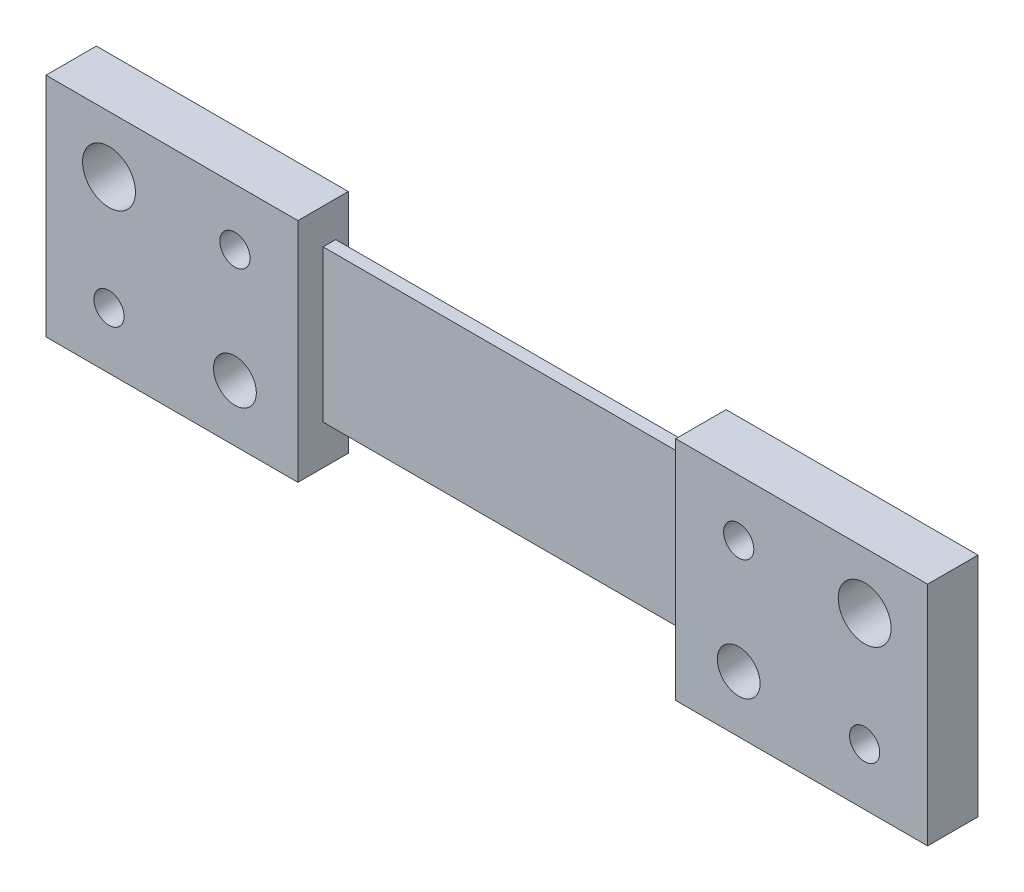
SolidWorks part; units mm, degrees
ref_plane "Спереди" through (0, 0, 0) normal (0, 0, 1) x (1, 0, 0)
ref_plane "Сверху" through (0, 0, 0) normal (0, 1, 0) x (1, 0, 0)
ref_plane "Справа" through (0, 0, 0) normal (1, 0, 0) x (0, 0, -1)
sketch "Эскиз1" plane through (0, 0, 0) normal (0, 0, 1) x (1, 0, 0)
  line L0 (-42.678, 0) -> (49.8614, 0) construction
  line L1 (0, 35.1777) -> (0, -24.4025) construction
  line L2 (15, -9) -> (15, 9)
  line L3 (-35, -9) -> (-15, -9)
  line L4 (-35, -9) -> (-35, 9)
  line L5 (-35, 9) -> (-15, 9)
  line L6 (-15, -9) -> (-15, 9)
  line L7 (35, 9) -> (15, 9)
  line L8 (35, -9) -> (35, 9)
  line L9 (35, -9) -> (15, -9)
  circle A0 centre (-30, 4.5) radius 2.1
  circle A1 centre (-20, 4.5) radius 1.2
  circle A2 centre (-20, -4.5) radius 1.7
  circle A3 centre (-30, -4.5) radius 1.2
  circle A4 centre (30, -4.5) radius 1.2
  circle A5 centre (20, -4.5) radius 1.7
  circle A6 centre (20, 4.5) radius 1.2
  circle A7 centre (30, 4.5) radius 2.1
  dimension "D4" = 4.5
  dimension "D6" = 4.2
  dimension "D7" = 5
  dimension "D8" = 4.5
  dimension "D9" = 2.4
  dimension "D11" = 4.5
  dimension "D12" = 5
  dimension "D13" = 4.5
  dimension "D14" = 3.4
  dimension "D1" = 20
  dimension "D2" = 18
  dimension "D3" = 35
  dimension "D5" = 5
  dimension "D10" = 5
extrude "Вытянуть1" add sketch "Эскиз1" along normal blind 4
cosmetic thread "Условное изображение резьбы1"
cosmetic thread "Условное изображение резьбы2"
cosmetic thread "Условное изображение резьбы3"
cosmetic thread "Условное изображение резьбы4"
cosmetic thread "Условное изображение резьбы5"
cosmetic thread "Условное изображение резьбы6"
cosmetic thread "Условное изображение резьбы7"
cosmetic thread "Условное изображение резьбы8"
ref_plane "Плоскость1" through (0, 0, 2) normal (0, 0, -1) x (-1, 0, 0)
sketch "Эскиз2" plane through (0, 0, 2) normal (0, 0, -1) x (-1, 0, 0)
  line L1 (-16.5252, -5.8577) -> (16.5981, -5.8577)
  line L2 (-16.5252, -5.8577) -> (-16.5252, 6.1948)
  line L3 (-16.5252, 6.1948) -> (16.5981, 6.1948)
  line L4 (16.5981, -5.8577) -> (16.5981, 6.1948)
extrude "Вытянуть2" add sketch "Эскиз2" along normal blind 1
